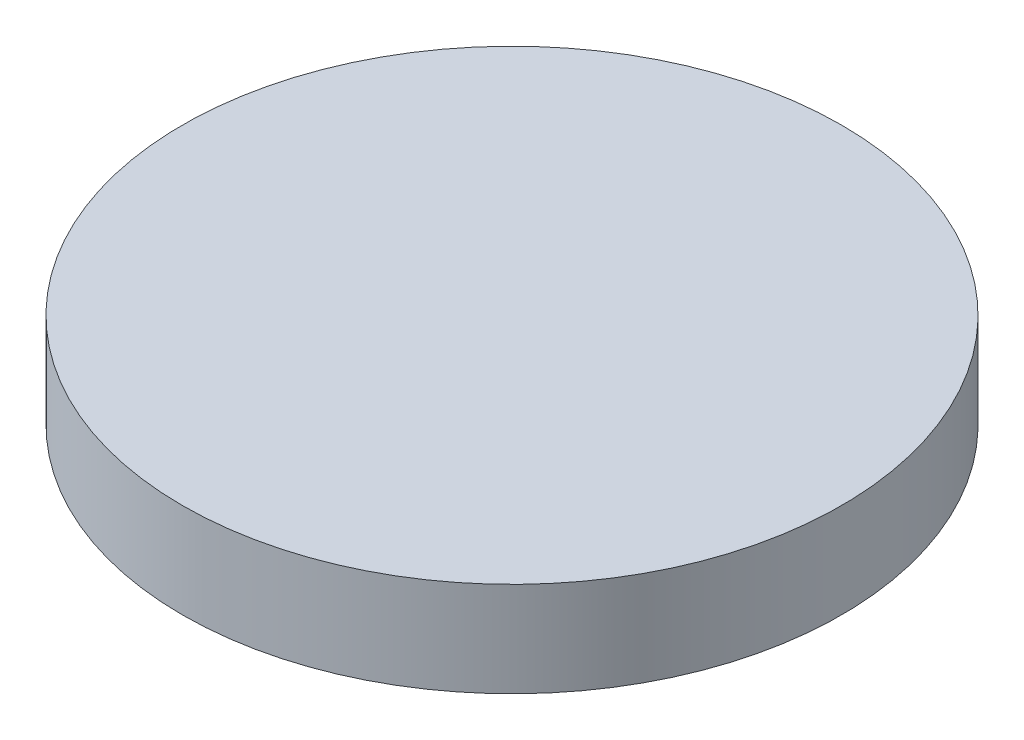
SolidWorks part; units mm, degrees
material "Brass"
ref_plane "Front Plane" through (0, 0, 0) normal (0, 0, 1) x (1, 0, 0)
ref_plane "Top Plane" through (0, 0, 0) normal (0, 1, 0) x (1, 0, 0)
ref_plane "Right Plane" through (0, 0, 0) normal (1, 0, 0) x (0, 0, -1)
sketch "Sketch1" plane through (0, 0, 0) normal (0, 1, 0) x (1, 0, 0)
  circle A0 centre (0, 0) radius 11.2
  dimension "D1" = 22.4
extrude "Boss-Extrude1" add sketch "Sketch1" against normal blind 3.22
